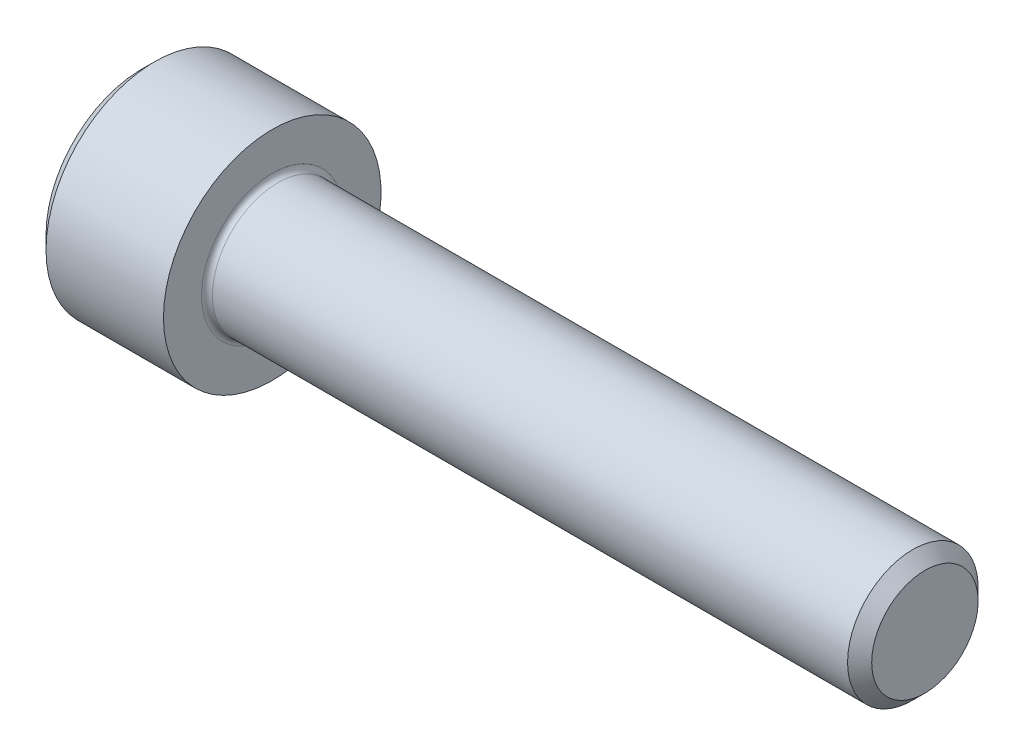
SolidWorks part; units mm, degrees
revolve "Base-Revolve" add sketch "BodySke"
sketch "BodySke" plane through (0, 0, 0) normal (0, 0, 1) x (1, 0, 0)
  line L0 (0, 0) -> (0, 4.4)
  line L1 (0.6, 5) -> (6, 5)
  line L2 (6, 5) -> (6, 3)
  line L3 (6, 3) -> (35.4455, 3)
  line L4 (36, 2.4455) -> (36, 0)
  line L5 (36, 0) -> (0, 0)
  line L6 (-31.75, 0) -> (127, 0) construction
  line L7 (0, 4.4) -> (0.6, 5)
  line L8 (36, 2.4455) -> (35.4455, 3)
  line L9 (0, -4.4) -> (0.6, -5) construction
  line L10 (36, -2.4455) -> (35.4455, -3) construction
  line L11 (7, 9.525) -> (7, 3.175) construction
  line L12 (6, 9.525) -> (6, 3.175) construction
  line L13 (-14, 9.525) -> (-14, 3.175) construction
  dimension "Diameter" = 6
  dimension "Head_ht" = 6
  dimension "Length" = 30
  dimension "Body_ch_ang" = 45
  dimension "Head_dia" = 10
  dimension "Head_ch_ang" = 45
  dimension "Minor_dia" = 4.891
  dimension "Advance" = 1
  dimension "Thread_nom" = 30
  dimension "Thread_length" = 50
  dimension "Head_ch_ht" = 0.6
cosmetic thread "ThreadCosmetic" [suppressed]
fillet "Fillet1" radius 0.25 1 edges at (6, 0, 3)
ref_plane "Plane1" through (0, 0, 0) normal (0, 0, 1) x (1, 0, 0)
ref_plane "Plane2" through (0, 0, 0) normal (0, 1, 0) x (1, 0, 0)
ref_plane "Plane3" through (0, 0, 0) normal (1, 0, 0) x (0, 0, -1)
sketch "Sketch2" plane through (0, 0, 0) normal (0, 0, 1) x (1, 0, 0)
  line L0 (0, 2.542) -> (3, 2.542)
  line L1 (3, 2.542) -> (4.4676, 0)
  line L2 (-31.75, 0) -> (127, 0) construction
  line L3 (4.4676, 0) -> (0, 0)
  line L4 (0, 0) -> (0, 2.542)
  line L5 (0, 4.4) -> (0, -4.4) construction
  line L6 (0, 0) -> (47.625, 0) construction
  line L7 (6, -5) -> (6, 5) construction
  dimension "D2" = 60
revolve "Hex-PreBroach" cut sketch "Sketch2" angle 360 about L6
sketch "Sketch3" plane through (0, 0, 0) normal (-1, 0, 0) x (0, 0.5, 0.866)
  line L0 (1.4676, 2.542) -> (-1.4676, 2.542)
  line L1 (-1.4676, 2.542) -> (-2.9352, 0)
  line L2 (1.4676, 2.542) -> (2.9352, 0)
  line L3 (1.4676, -2.542) -> (2.9352, 0)
  line L4 (1.4676, -2.542) -> (-1.4676, -2.542)
  line L5 (-1.4676, -2.542) -> (-2.9352, 0)
extrude "Hex" cut sketch "Sketch3" against normal blind 3
sketch "Sketch4" plane through (0, 0, 0) normal (-1, 0, 0) x (0, 0, 1)
  line L0 (0, 0) -> (2.8067, 0)
  line L1 (0, 0) -> (6.1484, 3.5498) construction
  line L2 (0, 0) -> (1.4033, 2.4307)
  line L3 (2.3336, 0.614) -> (2.6851, 0.817)
  line L4 (1.6986, 1.7139) -> (2.0501, 1.9169)
  arc A0 (2.3336, 0.614) -> (1.6986, 1.7139) centre (0, 0) ccw
  arc A1 (2.8067, 0) -> (2.6851, 0.817) centre (0, 0) ccw
  arc A2 (1.4033, 2.4307) -> (2.0501, 1.9169) centre (0, 0) cw
  dimension "D1" = 30
  dimension "D2" = 60
extrude "Spline" [suppressed] cut sketch "Sketch4" against normal blind 3
pattern_circular "CirPattern1" [suppressed] count 6 every 60
sketch "Sketch5" plane through (0, 0, 0) normal (0, 0, 1) x (1, 0, 0)
  line L0 (-31.75, 0) -> (127, 0) construction
  line L2 (0, 4.4) -> (0, -4.4) construction
  circle A0 centre (2.3, 0) radius 0.675
  dimension "Drilled_hole_dia" = 1.35
  dimension "Drilled_hole_loc" = 2.3
extrude "Hole" [suppressed] cut sketch "Sketch5" against normal through all and the other way through all
pattern_circular "Drilled-4" [suppressed] count 2 every 60
pattern_circular "Drilled-6" [suppressed] count 3 every 60
sketch "ThdSchSke" plane through (0, 0, 0) normal (0, 0, 1) x (1, 0, 0)
  line L0 (7, -2.4455) -> (6.6117, -3)
  line L1 (7, -2.4455) -> (7.3883, -3)
  line L2 (7.3883, -3) -> (7.3883, -3.75)
  line L3 (-3.175, 0) -> (5.1513, 0) construction
  line L5 (7.3883, -3.75) -> (6.6117, -3.75)
  line L6 (6.6117, -3.75) -> (6.6117, -3)
  line L7 (0, 4.4) -> (0, -4.4) construction
revolve "ThreadSchematic" [suppressed] cut sketch "ThdSchSke" angle 360 about L3
pattern_linear "ThdSchPat" [suppressed]
equation "\"D2@Sketch3\" = \"Hex_size@Sketch3\" / 2"
equation "\"D1@Sketch3\" = \"Hex_size@Sketch3\" / 2"
equation "\"D1@Sketch2\" = \"Hex_size@Sketch3\" / 2"
equation "\"D3@Sketch4\" = \"Spline_p_dim@Sketch4\" / 2"
equation "\"Thread_minor@ThreadCosmetic\"  =  \"Minor_dia@BodySke\""
equation "\"D2@CirPattern1\" = 360 / \"Num_teeth@CirPattern1\""
equation "\"Wall_thickness@Sketch2\" = \"Head_ht@BodySke\" - \"Key_eng@Hex\""
equation "\"Thread_length@ThreadCosmetic\" = ((sgn( (\"Length@BodySke\" - \"Advance@BodySke\" ) - \"Thread_nom@BodySke\" )-1)*( (\"Length@BodySke\" - \"Advance@BodySke\" ) - \"Thread_nom@BodySke\" ))/-2+ \"Thread_nom@BodySke\""
equation "\"Thread_minor@ThdSchSke\" = \"Minor_dia@BodySke\""
equation "\"Diameter@ThdSchSke\" = \"Diameter@BodySke\""
equation "\"Overcut@ThdSchSke\" = \"Diameter@BodySke\" * 1.25"
equation "\"Start@ThdSchSke\" = \"Head_ht@BodySke\" + \"Length@BodySke\" - \"Thread_length@ThreadCosmetic\"  '---Non-countersunk---"
equation "\"Num_threads@ThdSchPat\" = int( \"Thread_length@ThreadCosmetic\" / \"Advance@BodySke\" + 0.999 )  + 1"
equation "\"Advance@ThdSchPat\" = \"Thread_length@ThreadCosmetic\" /  (\"Num_threads@ThdSchPat\" - 1) 'relax it"
equation "\"Num_threads@ThdSchPat\" = \"Num_threads@ThdSchPat\" - sgn( \"Num_threads@ThdSchPat\" - 1) '---chamfered tips only---"
